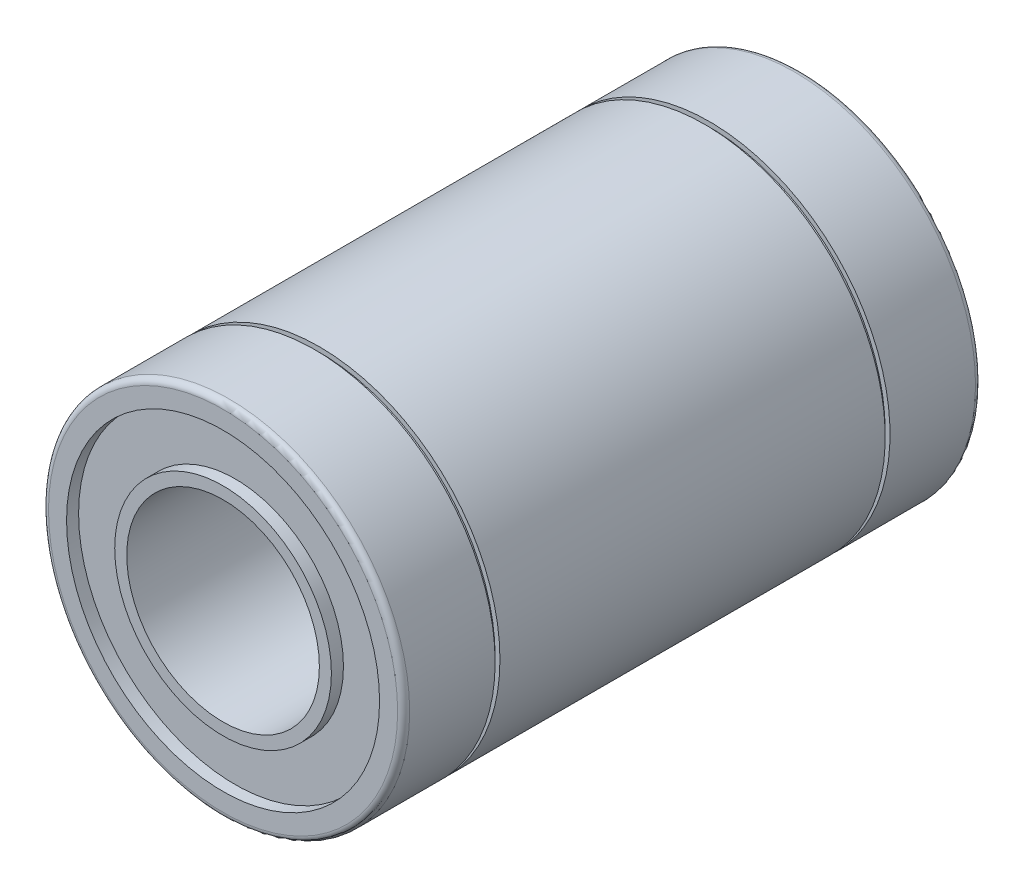
SolidWorks part; units mm, degrees
ref_plane "Plano frontal" through (0, 0, 0) normal (0, 0, 1) x (1, 0, 0)
ref_plane "Plano superior" through (0, 0, 0) normal (0, 1, 0) x (1, 0, 0)
ref_plane "Plano direito" through (0, 0, 0) normal (1, 0, 0) x (0, 0, -1)
sketch "Esboço1" plane through (0, 0, 0) normal (0, 0, 1) x (1, 0, 0)
  circle A0 centre (0, 0) radius 4
  circle A1 centre (0, 0) radius 7.5
  dimension "D1" = 8
  dimension "D2" = 15
extrude "Ressalto-extrusão1" add sketch "Esboço1" along normal mid plane 24
sketch "Esboço2" plane through (0, 0, 12) normal (0, 0, 1) x (1, 0, 0)
  circle A0 centre (0, 0) radius 4.5
  circle A1 centre (0, 0) radius 6.5
  circle A2 centre (0, 0) radius 7.5 construction
  circle A3 centre (0, 0) radius 4 construction
  dimension "D1" = 1
  dimension "D2" = 0.5
extrude "Corte-extrusão1" cut sketch "Esboço2" against normal blind 0.5
sketch "Esboço3" plane through (0, 0, -12) normal (0, 0, -1) x (-1, 0, 0)
  circle A0 centre (0, 0) radius 4.5
  circle A1 centre (0, 0) radius 6.5
  circle A2 centre (0, 0) radius 4 construction
  circle A3 centre (0, 0) radius 7.5 construction
  dimension "D1" = 0.5
  dimension "D2" = 1
extrude "Corte-extrusão2" cut sketch "Esboço3" against normal blind 0.5
ref_plane "Plano1" through (0, 0, 8) normal (0, 0, 1) x (1, 0, 0)
sketch "Esboço4" plane through (0, 0, 8) normal (0, 0, 1) x (1, 0, 0)
  circle A0 centre (0, 0) radius 8.1502
  circle A1 centre (0, 0) radius 7.3
  circle A2 centre (0, 0) radius 7.5 construction
  dimension "D1" = 0.2
extrude "Corte-extrusão3" cut sketch "Esboço4" along normal blind 0.2
mirror "Espelhar1" about plane through (0, 0, 0) normal (0, 0, 1) of "Corte-extrusão3"
fillet "Filete1" radius 0.25 2 edges at (7.5, 0, -12) (7.5, 0, 12)
